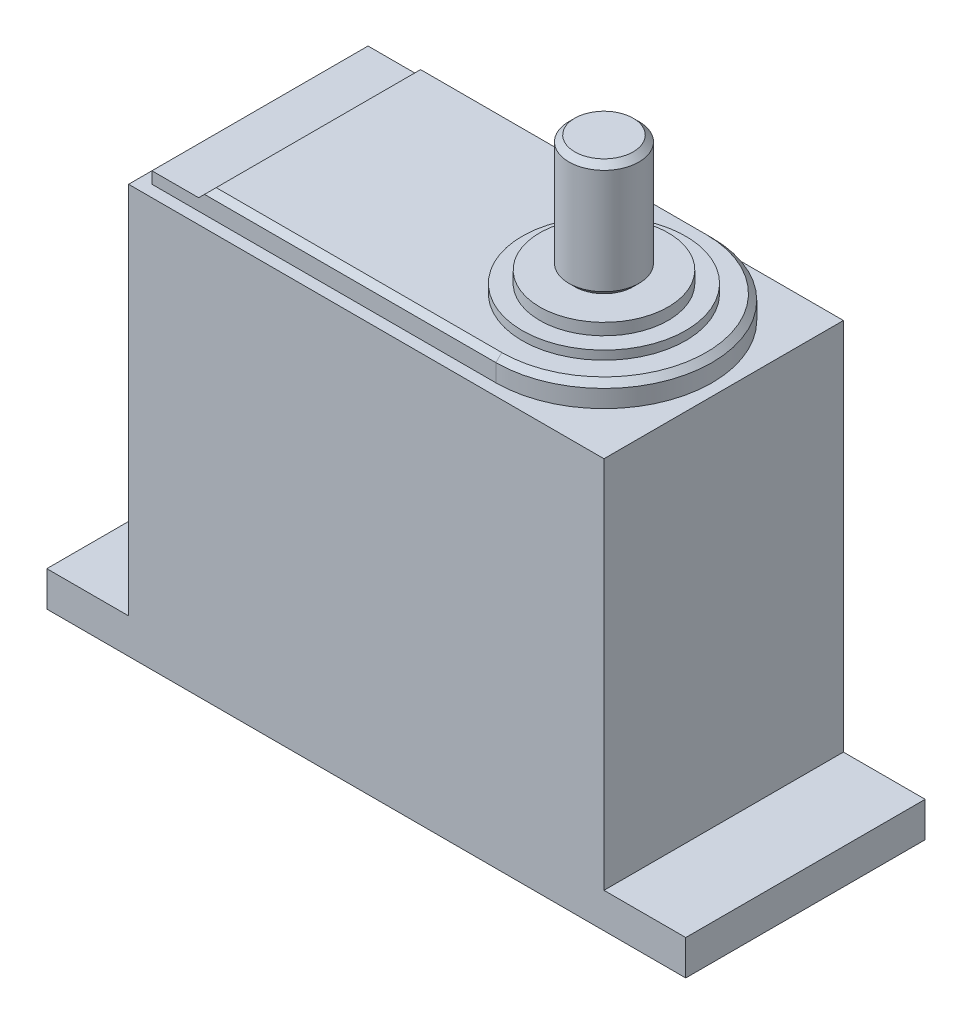
SolidWorks part; units mm, degrees
ref_plane "Front Plan" through (0, 0, 0) normal (0, 0, 1) x (1, 0, 0)
ref_plane "Top Plan" through (0, 0, 0) normal (0, 1, 0) x (1, 0, 0)
ref_plane "Right Plan" through (0, 0, 0) normal (1, 0, 0) x (0, 0, -1)
sketch "Sketch 1" plane through (0, 0, 0) normal (0, 0, 1) x (1, 0, 0)
  line L1 (-20.35, -17.5) -> (20.35, -17.5)
  line L2 (-20.35, -17.5) -> (-20.35, 17.5)
  line L3 (-20.35, 17.5) -> (20.35, 17.5)
  line L4 (20.35, -17.5) -> (20.35, 17.5)
  line L5 (-20.35, -17.5) -> (20.35, 17.5) construction
  line L6 (-20.35, 17.5) -> (20.35, -17.5) construction
  point P0 (0, 0)
  dimension "D1" = 40.7
  dimension "D2" = 35
extrude "Extrude Boss" add sketch "Sketch 1" along normal mid plane 20.5
ref_plane "Plan 1" through (0, 0, 9.25) normal (0, 0, 1) x (1, 0, 0)
sketch "Sketch 2" plane through (0, 0, 9.25) normal (0, 0, 1) x (1, 0, 0)
  line L1 (-20.35, 13) -> (-27.35, 13)
  line L2 (-20.35, 13) -> (-20.35, 10.5)
  line L3 (-20.35, 10.5) -> (-27.35, 10.5)
  line L4 (-27.35, 13) -> (-27.35, 10.5)
  line L5 (-20.35, -17.5) -> (20.35, -17.5) construction
  line L6 (0, 17.5) -> (0, -17.5) construction
  line L7 (20.35, 17.5) -> (-20.35, 17.5) construction
  line L8 (20.35, 13) -> (20.35, 10.5)
  line L9 (20.35, 10.5) -> (27.35, 10.5)
  line L10 (27.35, 13) -> (27.35, 10.5)
  line L11 (20.35, 13) -> (27.35, 13)
  line L12 (-20.35, 17.5) -> (-20.35, -17.5) construction
  dimension "D1" = 2.5
  dimension "D2" = 7
  dimension "D3" = 28
sketch "Sketch 3" plane through (0, 17.5, 0) normal (0, 1, 0) x (1, 0, 0)
  line L1 (20.35, 10.25) -> (-20.35, 10.25) construction
  line L2 (-20.35, -10.25) -> (-20.35, 10.25) construction
  line L3 (20.35, -10.25) -> (-20.35, -10.25) construction
  line L4 (20.35, -10.25) -> (20.35, 10.25) construction
  line L5 (20.35, 10.25) -> (-20.35, 10.25) construction
  line L6 (-20.35, -10.25) -> (-20.35, 10.25) construction
  line L7 (20.35, -10.25) -> (-20.35, -10.25) construction
  line L8 (20.35, -10.25) -> (20.35, 10.25) construction
  line L9 (10.1, 9.25) -> (-19.35, 9.25)
  line L10 (-19.35, -9.25) -> (-19.35, 9.25)
  line L11 (10.1, -9.25) -> (-19.35, -9.25)
  line L12 (19.35, -9.25) -> (19.35, 9.25) construction
  line L13 (19.35, 9.25) -> (-19.35, 9.25) construction
  line L14 (19.35, -9.25) -> (-19.35, -9.25) construction
  arc A0 (10.1, -9.25) -> (10.1, 9.25) centre (10.1, 0) ccw
  dimension "D1" = 1
extrude "Extrude 2" add sketch "Sketch 3" along normal blind 2
sketch "Sketch 4" plane through (0, 0, 9.25) normal (0, 0, 1) x (1, 0, 0)
  line L0 (-19.35, 19.5) -> (-19.35, 18.5)
  line L2 (-19.35, 18.5) -> (-15.35, 18.5)
  line L3 (-15.35, 18.5) -> (-14.35, 19.5)
  line L5 (-14.35, 19.5) -> (-19.35, 19.5)
  line L7 (-19.35, 19.5) -> (-19.35, 17.5) construction
  line L8 (-19.35, 19.5) -> (10.1, 19.5) construction
  dimension "D1" = 5
  dimension "D2" = 45
extrude "Extrude Cut" cut sketch "Sketch 4" against normal up to vertex (18.5 mm away)
sketch "Croquis10" plane through (0, 19.5, 0) normal (0, 1, 0) x (1, 0, 0)
  circle A1 centre (10.1, 0) radius 7
  arc A2 (10.1, -9.25) -> (10.1, 9.25) centre (10.1, 0) ccw construction
  dimension "D1" = 14
extrude "Saliente-Extruir5" add sketch "Croquis10" along normal blind 0.75
sketch "Croquis11" plane through (0, 20.25, 0) normal (0, 1, 0) x (1, 0, 0)
  circle A0 centre (10.1, 0) radius 5.5
  circle A1 centre (10.1, 0) radius 7
  circle A2 centre (10.1, 0) radius 7 construction
  dimension "D1" = 0
  dimension "D2" = 1.5
extrude "Saliente-Extruir6" add sketch "Croquis11" along normal blind 1
sketch "Croquis12" plane through (0, 21.25, 0) normal (0, 1, 0) x (1, 0, 0)
  circle A0 centre (10.1, 0) radius 3
  circle A1 centre (10.1, 0) radius 5.5 construction
  dimension "D1" = 6
extrude "Saliente-Extruir7" add sketch "Croquis12" along normal blind 10
chamfer "Chaflán2" distance 0.5 angle 45 4 edges at (-2.125, 19.5, -9.25) (19.35, 19.5, 0) (-2.125, 19.5, 9.25) (10.1, 31.25, 3)
sketch "Croquis13" plane through (0, 0, 0) normal (0, 0, 1) x (1, 0, 0)
  line L0 (7.1, 21.75) -> (7.1, 21.25)
  line L1 (7.1, 30.75) -> (7.1, 21.25) construction
  line L2 (7.1, 21.25) -> (7.6, 21.25)
  line L3 (15.6, 21.25) -> (4.6, 21.25) construction
  line L4 (7.6, 21.25) -> (7.1, 21.75)
  line L5 (7.6, 31.25) -> (7.1, 30.75) construction
  line L6 (10.1, 31.25) -> (10.1, 21.25) construction
  line L7 (12.6, 31.25) -> (7.6, 31.25) construction
revolve "Cortar-Revolución1" cut sketch "Croquis13" angle 360 about L6
sketch "Sketch1" plane through (0, -17.5, 0) normal (0, -1, 0) x (1, 0, 0)
  line L0 (0, 10.25) -> (0, -10.25) construction
  line L1 (-20.35, 10.25) -> (-27.35, 10.25)
  line L2 (-20.35, 10.25) -> (-20.35, -10.25)
  line L3 (-20.35, -10.25) -> (-27.35, -10.25)
  line L4 (-27.35, 10.25) -> (-27.35, -10.25)
  line L5 (-20.35, 10.25) -> (20.35, 10.25) construction
  line L6 (-20.35, -10.25) -> (20.35, -10.25) construction
  line L7 (20.35, 10.25) -> (20.35, -10.25)
  line L8 (20.35, -10.25) -> (27.35, -10.25)
  line L9 (27.35, 10.25) -> (27.35, -10.25)
  line L10 (20.35, 10.25) -> (27.35, 10.25)
  dimension "D1" = 7
extrude "Boss-Extrude1" add sketch "Sketch1" against normal blind 3
